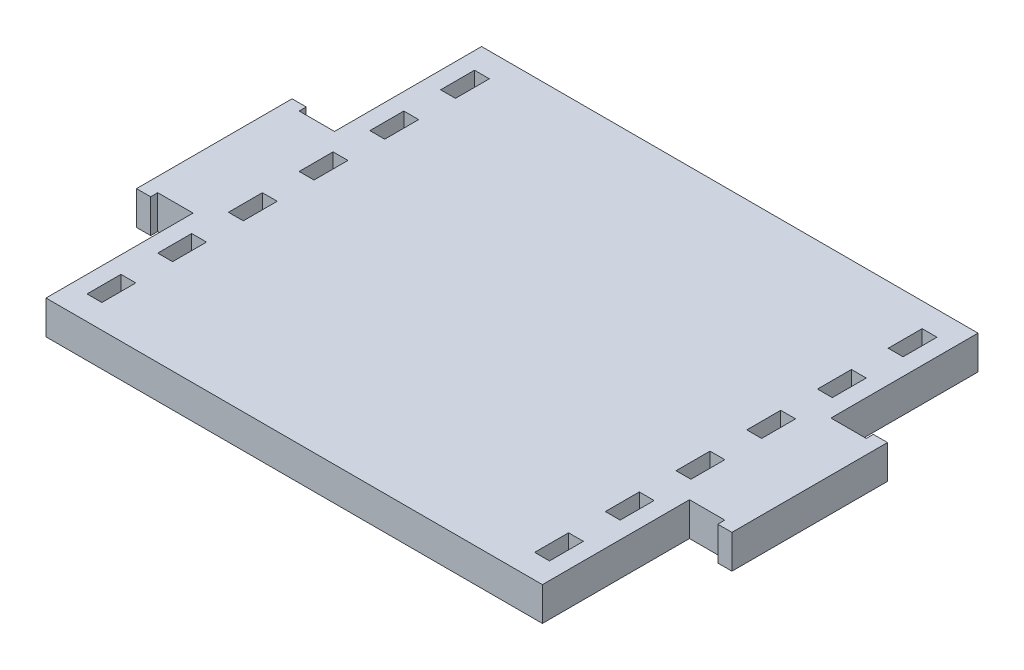
SolidWorks part; units mm, degrees
ref_plane "Front Plane" through (0, 0, 0) normal (0, 0, 1) x (1, 0, 0)
ref_plane "Top Plane" through (0, 0, 0) normal (0, 1, 0) x (1, 0, 0)
ref_plane "Right Plane" through (0, 0, 0) normal (1, 0, 0) x (0, 0, -1)
sketch "Sketch1" plane through (0, 0, 0) normal (0, 1, 0) x (1, 0, 0)
  line L0 (0, 39.116) -> (0, -39.116) construction
  line L1 (-44.577, 39.116) -> (44.577, 39.116)
  line L2 (-44.577, 39.116) -> (-44.577, -39.116)
  line L3 (-44.577, -39.116) -> (44.577, -39.116)
  line L4 (44.577, 39.116) -> (44.577, -39.116)
  line L5 (-44.577, 12.7) -> (-50.927, 12.7)
  line L6 (-44.577, 12.7) -> (-44.577, -12.7)
  line L7 (-44.577, -12.7) -> (-50.927, -12.7)
  line L8 (-50.927, 12.7) -> (-50.927, -12.7)
  line L9 (44.577, -12.7) -> (50.927, -12.7)
  line L10 (50.927, 12.7) -> (50.927, -12.7)
  line L11 (44.577, 12.7) -> (50.927, 12.7)
  line L12 (44.577, 12.7) -> (44.577, -12.7)
  point P4 (0, 39.116)
  point P6 (-44.577, 0)
  point P11 (-50.927, 0)
  dimension "D1" = 89.154
  dimension "D2" = 78.232
  dimension "D3" = 6.35
  dimension "D4" = 25.4
extrude "Boss-Extrude1" add sketch "Sketch1" along normal mid plane 6.0452 contours L0 L1 L2 L3 | L5 L8 L7 L2 | L1 L0 L3 L4 | L11 L4 L9 L10
sketch "Sketch4" plane through (0, 3.0226, 0) normal (0, 1, 0) x (1, 0, 0)
  line L0 (-41.529, -34.798) -> (-38.862, -34.798)
  line L1 (-41.529, -34.798) -> (-41.529, -28.702)
  line L2 (-41.529, -28.702) -> (-38.862, -28.702)
  line L3 (-38.862, -34.798) -> (-38.862, -28.702)
  line L4 (-44.577, -12.7) -> (-44.577, -39.116) construction
  line L5 (-44.577, -39.116) -> (44.577, -39.116) construction
  line L6 (-41.529, -22.098) -> (-38.862, -22.098)
  line L7 (-38.862, -22.098) -> (-38.862, -16.002)
  line L8 (-41.529, -16.002) -> (-38.862, -16.002)
  line L9 (-41.529, -22.098) -> (-41.529, -16.002)
  line L10 (-41.529, -9.398) -> (-38.862, -9.398)
  line L11 (-38.862, -9.398) -> (-38.862, -3.302)
  line L12 (-41.529, -3.302) -> (-38.862, -3.302)
  line L13 (-41.529, -9.398) -> (-41.529, -3.302)
  line L14 (-41.529, 3.302) -> (-38.862, 3.302)
  line L15 (-38.862, 3.302) -> (-38.862, 9.398)
  line L16 (-41.529, 9.398) -> (-38.862, 9.398)
  line L17 (-41.529, 3.302) -> (-41.529, 9.398)
  line L18 (-41.529, 16.002) -> (-38.862, 16.002)
  line L19 (-38.862, 16.002) -> (-38.862, 22.098)
  line L20 (-41.529, 22.098) -> (-38.862, 22.098)
  line L21 (-41.529, 16.002) -> (-41.529, 22.098)
  line L22 (-41.529, 28.702) -> (-38.862, 28.702)
  line L23 (-38.862, 28.702) -> (-38.862, 34.798)
  line L24 (-41.529, 34.798) -> (-38.862, 34.798)
  line L25 (-41.529, 28.702) -> (-41.529, 34.798)
  line L26 (38.862, -22.098) -> (41.529, -22.098)
  line L27 (41.529, -22.098) -> (41.529, -16.002)
  line L28 (38.862, -16.002) -> (41.529, -16.002)
  line L29 (38.862, -22.098) -> (38.862, -16.002)
  line L30 (38.862, -9.398) -> (41.529, -9.398)
  line L31 (41.529, -9.398) -> (41.529, -3.302)
  line L32 (38.862, -3.302) -> (41.529, -3.302)
  line L33 (38.862, -9.398) -> (38.862, -3.302)
  line L34 (38.862, 3.302) -> (41.529, 3.302)
  line L35 (41.529, 3.302) -> (41.529, 9.398)
  line L36 (38.862, 9.398) -> (41.529, 9.398)
  line L37 (38.862, 3.302) -> (38.862, 9.398)
  line L38 (38.862, 16.002) -> (41.529, 16.002)
  line L39 (41.529, 16.002) -> (41.529, 22.098)
  line L40 (38.862, 22.098) -> (41.529, 22.098)
  line L41 (38.862, 16.002) -> (38.862, 22.098)
  line L42 (38.862, 28.702) -> (41.529, 28.702)
  line L43 (41.529, 28.702) -> (41.529, 34.798)
  line L44 (38.862, 34.798) -> (41.529, 34.798)
  line L45 (38.862, 28.702) -> (38.862, 34.798)
  line L46 (38.862, -34.798) -> (41.529, -34.798)
  line L47 (41.529, -34.798) -> (41.529, -28.702)
  line L48 (38.862, -28.702) -> (41.529, -28.702)
  line L49 (38.862, -34.798) -> (38.862, -28.702)
  line L50 (-41.529, -34.798) -> (-41.529, -22.098) construction
  line L51 (-41.529, -34.798) -> (38.862, -34.798) construction
  dimension "D1" = 6.096
  dimension "D2" = 2.667
  dimension "D3" = 3.048
  dimension "D4" = 4.318
  dimension "D5" = 12.7
  dimension "D6" = 80.391
  dimension "D7" = 6
  dimension "D8" = 2
extrude "Cut-Extrude2" cut sketch "Sketch4" against normal blind 6.0452
sketch "Sketch5" plane through (0, 3.0226, 0) normal (0, 1, 0) x (1, 0, 0)
  line L0 (-50.927, 12.7) -> (-50.927, -12.7) construction
  line L1 (-53.467, 13.97) -> (-50.927, 13.97)
  line L2 (-53.467, 13.97) -> (-53.467, -13.97)
  line L3 (-53.467, -13.97) -> (-50.927, -13.97)
  line L4 (-50.927, 13.97) -> (-50.927, -13.97)
  line L8 (0, 39.116) -> (0, -39.116) construction
  line L9 (-44.577, 39.116) -> (44.577, 39.116) construction
  line L10 (-44.577, -39.116) -> (44.577, -39.116) construction
  line L11 (53.467, -13.97) -> (50.927, -13.97)
  line L12 (50.927, 13.97) -> (50.927, -13.97)
  line L13 (53.467, 13.97) -> (50.927, 13.97)
  line L14 (53.467, 13.97) -> (53.467, -13.97)
  line L15 (-44.577, 12.7) -> (-50.927, 12.7) construction
  point P6 (-53.467, 0)
  dimension "D1" = 1.27
  dimension "D2" = 2.54
extrude "Boss-Extrude2" add sketch "Sketch5" against normal blind 6.0452
